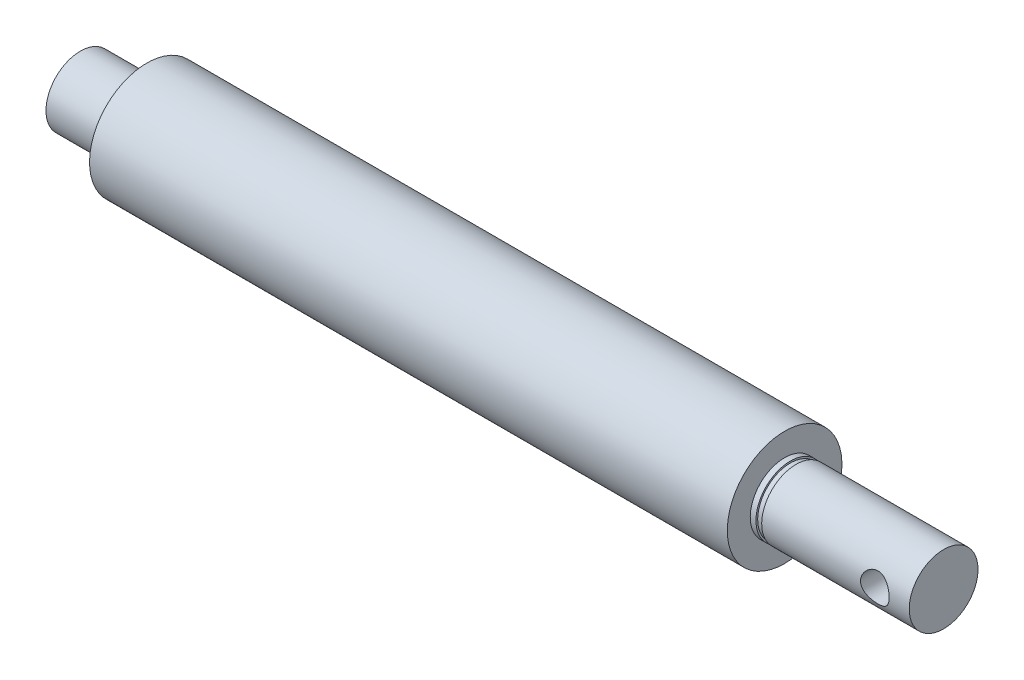
SolidWorks part; units mm, degrees
ref_plane "Front Plane" through (0, 0, 0) normal (0, 0, 1) x (1, 0, 0)
ref_plane "Top Plane" through (0, 0, 0) normal (0, 1, 0) x (1, 0, 0)
ref_plane "Right Plane" through (0, 0, 0) normal (1, 0, 0) x (0, 0, -1)
sketch "Sketch1" plane through (0, 0, 0) normal (0, 0, 1) x (1, 0, 0)
  line L0 (0, 0) -> (75.3, 0)
  line L1 (75.3, 0) -> (75.3, 3)
  line L2 (75.3, 3) -> (62.43, 3)
  line L3 (62.43, 3) -> (62.43, 2.85)
  line L4 (62.43, 2.85) -> (61.93, 2.85)
  line L5 (61.93, 2.85) -> (61.93, 3)
  line L6 (61.93, 3) -> (61.43, 3)
  line L7 (61.43, 3) -> (61.43, 5)
  line L8 (61.43, 5) -> (5.8, 5)
  line L9 (5.8, 5) -> (5.8, 3)
  line L10 (5.8, 3) -> (5.3, 3)
  line L11 (5.3, 3) -> (5.3, 2.85)
  line L12 (5.3, 2.85) -> (4.8, 2.85)
  line L13 (4.8, 2.85) -> (4.8, 3)
  line L14 (4.8, 3) -> (0, 3)
  line L15 (0, 3) -> (0, 0)
  dimension "D1" = 75.3
  dimension "D2" = 0.5
  dimension "D3" = 0.5
  dimension "D4" = 0.15
  dimension "D5" = 4.8
  dimension "D6" = 0.5
  dimension "D7" = 2
  dimension "D8" = 3
  dimension "D9" = 55.63
revolve "Revolve1" add sketch "Sketch1" angle 360 about L0
sketch "Sketch2" plane through (75.3, 0, 0) normal (1, 0, 0) x (0, 0, -1)
  line L0 (0, 3) -> (0, -3) construction
  circle A0 centre (0, 0) radius 3 construction
  circle A1 centre (0, 0) radius 3 construction
sketch "Sketch3" plane through (61.43, 0, 0) normal (1, 0, 0) x (0, 0, -1)
  line L0 (0, 3) -> (0, -3) construction
ref_plane "Plane1" through (0, 0, 0) normal (0, 0, -1) x (-1, 0, 0)
sketch "Sketch4" plane through (0, 0, 0) normal (0, 0, -1) x (-1, 0, 0)
  line L0 (-75.3, 3) -> (-75.3, -3) construction
  circle A0 centre (-72.3, 0) radius 1.25
  dimension "D1" = 2.5
  dimension "D2" = 3
extrude "Cut-Extrude1" cut sketch "Sketch4" against normal mid plane 10
